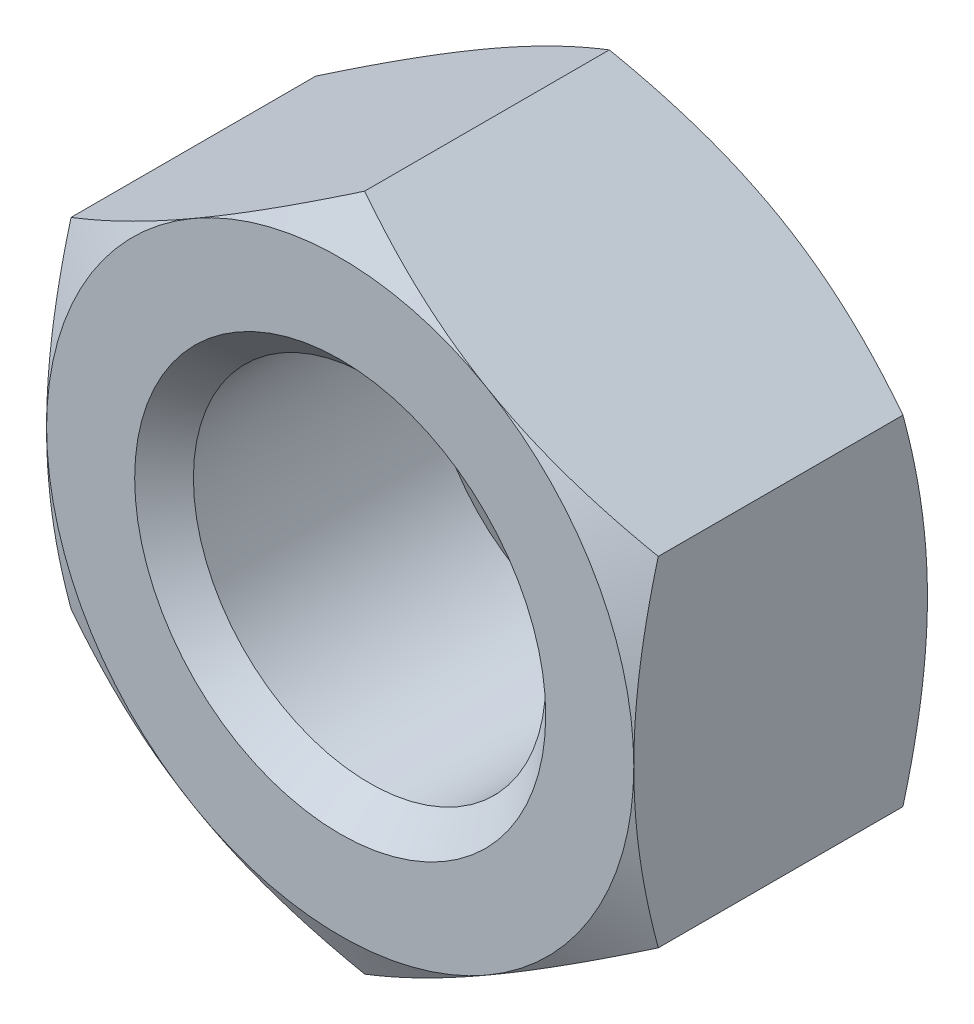
SolidWorks part; units mm, degrees
material "Plain Carbon Steel"
ref_plane "Front Plane" through (0, 0, 0) normal (0, 0, 1) x (1, 0, 0)
ref_plane "Top Plane" through (0, 0, 0) normal (0, 1, 0) x (1, 0, 0)
ref_plane "Right Plane" through (0, 0, 0) normal (1, 0, 0) x (0, 0, -1)
sketch "Sketch1" plane through (0, 0, 0) normal (0, 0, 1) x (1, 0, 0)
  line L1 (0, -5.7735) -> (5, -2.8868)
  line L2 (5, -2.8868) -> (5, 2.8868)
  line L3 (5, 2.8868) -> (0, 5.7735)
  line L4 (0, 5.7735) -> (-5, 2.8868)
  line L5 (-5, 2.8868) -> (-5, -2.8868)
  line L6 (-5, -2.8868) -> (0, -5.7735)
  circle A0 centre (0, 0) radius 5 construction
  circle A1 centre (0, 0) radius 3
  dimension "D2" = 6
  dimension "D1" = 10
extrude "Boss-Extrude1" add sketch "Sketch1" along normal blind 5
sketch "Sketch2" plane through (0, 0, 0) normal (1, 0, 0) x (0, 0, -1)
  line L0 (-5, 5.7735) -> (-5, 5)
  line L1 (-5, 2.8868) -> (-5, 5.7735) construction
  line L2 (-5, 5) -> (-4.5833, 5.7735)
  line L3 (-5, 5.7735) -> (0, 5.7735) construction
  line L4 (-4.5833, 5.7735) -> (-5, 5.7735)
  line L5 (-0.4167, 5.7735) -> (0, 5.7735)
  line L6 (0, 5.7735) -> (0, 5)
  line L7 (0, 2.8868) -> (0, 5.7735) construction
  line L8 (0, 5) -> (-0.4167, 5.7735)
  line L9 (-4.5833, 5.7735) -> (-4.1667, 5.7735) construction
  line L10 (-4.1667, 5.7735) -> (-3.75, 5.7735) construction
  line L11 (-3.75, 5.7735) -> (-3.3333, 5.7735) construction
  line L12 (-3.3333, 5.7735) -> (-2.9167, 5.7735) construction
  line L13 (-2.9167, 5.7735) -> (-2.5, 5.7735) construction
  line L14 (-2.5, 5.7735) -> (-2.0833, 5.7735) construction
  line L15 (-2.0833, 5.7735) -> (-1.6667, 5.7735) construction
  line L16 (-1.6667, 5.7735) -> (-1.25, 5.7735) construction
  line L17 (-1.25, 5.7735) -> (-0.8333, 5.7735) construction
  line L18 (0, 0) -> (-5, 0) construction
  line L19 (-5, -2.8868) -> (-5, 2.8868) construction
  line L20 (-5, 3) -> (-4.5, 3)
  line L21 (-4.5, 3) -> (-5, 3.5)
  line L22 (-5, 3.5) -> (-5, 3)
  line L23 (0, 3) -> (-0.5, 3)
  line L24 (0, -2.8868) -> (0, 2.8868) construction
  line L25 (-0.5, 3) -> (0, 3.5)
  line L26 (0, 3.5) -> (0, 3)
  line L29 (-4.5, 3) -> (-4, 3) construction
  line L30 (-4, 3) -> (-3.5, 3) construction
  line L31 (-3.5, 3) -> (-3, 3) construction
  line L32 (-3, 3) -> (-2.5, 3) construction
  line L33 (-2.5, 3) -> (-2, 3) construction
  line L34 (-2, 3) -> (-1.5, 3) construction
  line L35 (-1.5, 3) -> (-1, 3) construction
  line L36 (-1, 3) -> (-0.5, 3) construction
  line L37 (-0.8333, 5.7735) -> (-0.4167, 5.7735) construction
  dimension "D1" = 10
revolve "Cut-Revolve1" cut sketch "Sketch2" angle 360 about L18
